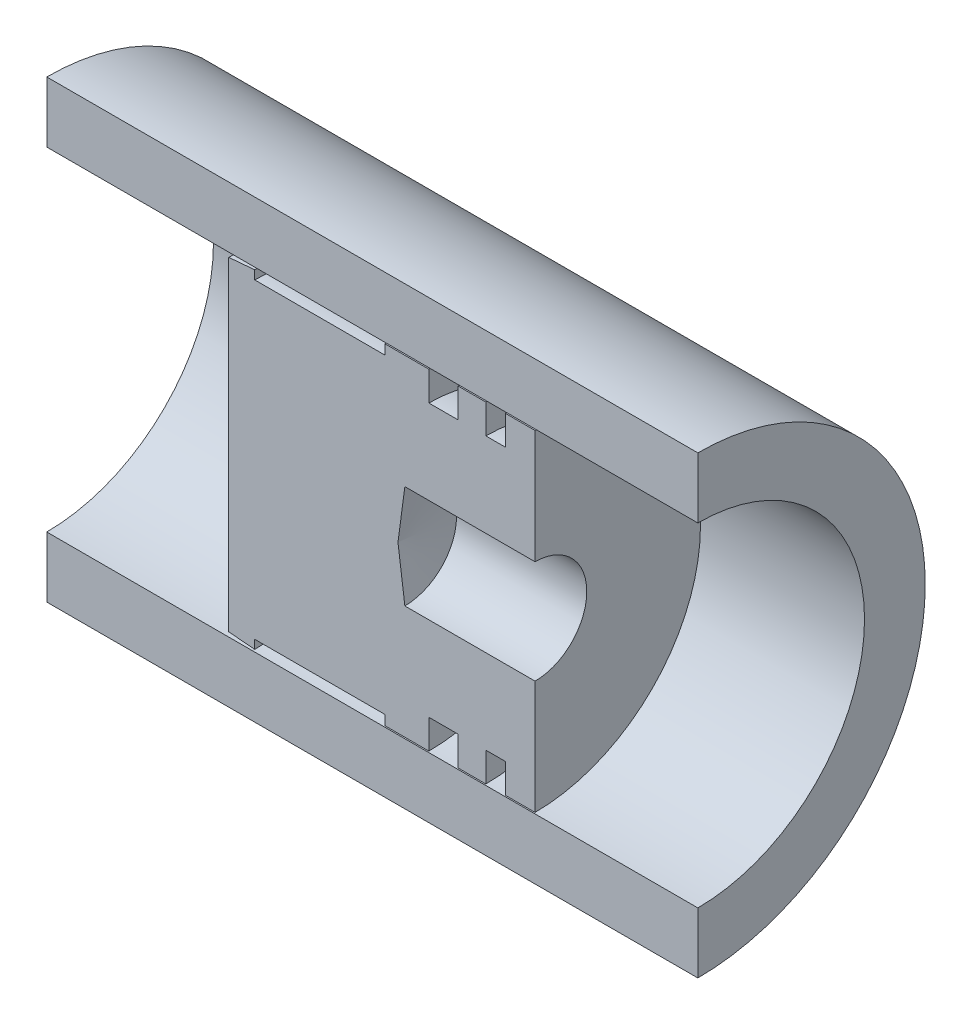
SolidWorks part; units mm, degrees
ref_plane "Front Plane" through (0, 0, 0) normal (0, 0, 1) x (1, 0, 0)
ref_plane "Top Plane" through (0, 0, 0) normal (0, 1, 0) x (1, 0, 0)
ref_plane "Right Plane" through (0, 0, 0) normal (1, 0, 0) x (0, 0, -1)
sketch "Sketch1" plane through (0, 0, 0) normal (0, 0, 1) x (1, 0, 0)
  line L0 (-43.06, 25.25) -> (-47.06, 24.9)
  line L1 (-47.06, 0) -> (-21.06, 0)
  line L2 (-47.06, 0) -> (-47.06, 24.9)
  line L3 (-23.06, 25.4) -> (-16.31, 25.4)
  line L4 (0, 7.9375) -> (0, 25.4)
  line L5 (-16.31, 25.4) -> (-16.31, 20.9)
  line L6 (-16.31, 20.9) -> (-11.81, 20.9)
  line L7 (-43.06, 25.25) -> (-43.06, 23.9)
  line L8 (-43.06, 23.9) -> (-23.06, 23.9)
  line L9 (-23.06, 25.4) -> (-23.06, 23.9)
  line L10 (-11.81, 20.9) -> (-11.81, 25.4)
  line L11 (-7.56, 25.4) -> (-7.56, 20.9)
  line L12 (-7.56, 20.9) -> (-4.56, 20.9)
  line L13 (-4.56, 20.9) -> (-4.56, 25.4)
  line L14 (-11.81, 25.4) -> (-7.56, 25.4)
  line L15 (-4.56, 25.4) -> (0, 25.4)
  line L17 (-20, 7.9375) -> (0, 7.9375)
  line L18 (-20, 7.9375) -> (-21.06, 0)
  dimension "D1" = 4
  dimension "D2" = 0.5
  dimension "D3" = 1.5
  dimension "D4" = 25.4
  dimension "D5" = 0.15
  dimension "D6" = 17.4625
  dimension "D7" = 20
  dimension "D8" = 4.5
  dimension "D9" = 4.5
  dimension "D10" = 4.5
  dimension "D11" = 3
  dimension "D12" = 6.75
  dimension "D13" = 4.25
  dimension "D14" = 7.9375
  dimension "D15" = 20
  dimension "D16" = 26
  dimension "D17" = 1.06
  dimension "D18" = 8.008
revolve "Revolve1" add sketch "Sketch1" angle 360 about L1
sketch "Sketch3" plane through (0, 0, 0) normal (0, 0, 1) x (1, 0, 0)
  line L1 (-75, 34.925) -> (25, 34.925)
  line L2 (-75, 34.925) -> (-75, 25.6)
  line L3 (-75, 25.6) -> (25, 25.6)
  line L4 (25, 34.925) -> (25, 25.6)
  dimension "D1" = 100
  dimension "D2" = 25
  dimension "D3" = 9.325
  dimension "D4" = 25.6
ref_axis "Axis1" through (-80, 0, 0) along (1, 0, 0)
revolve "Revolve2" add sketch "Sketch3" angle 360 about axis through (-80, 0, 0) along (1, 0, 0)
sketch "Sketch4" plane through (0, 0, 0) normal (0, 0, 1) x (1, 0, 0)
  line L1 (-84, 45) -> (35, 45)
  line L2 (-84, 45) -> (-84, -45)
  line L3 (-84, -45) -> (35, -45)
  line L4 (35, 45) -> (35, -45)
  dimension "D1" = 35
  dimension "D2" = 119
  dimension "D3" = 90
  dimension "D4" = 45
extrude "Cut-Extrude1" cut sketch "Sketch4" along normal through all
sketch "Sketch5" plane through (0, 0, 0) normal (0, 0, 1) x (1, 0, 0)
  line L1 (-85, 40) -> (30, 40)
  line L2 (-85, 40) -> (-85, -40)
  line L3 (-85, -40) -> (30, -40)
  line L4 (30, 40) -> (30, -40)
  dimension "D1" = 115
  dimension "D2" = 30
  dimension "D3" = 80
  dimension "D4" = 40
extrude "Cut-Extrude2" cut sketch "Sketch5" along normal through all
